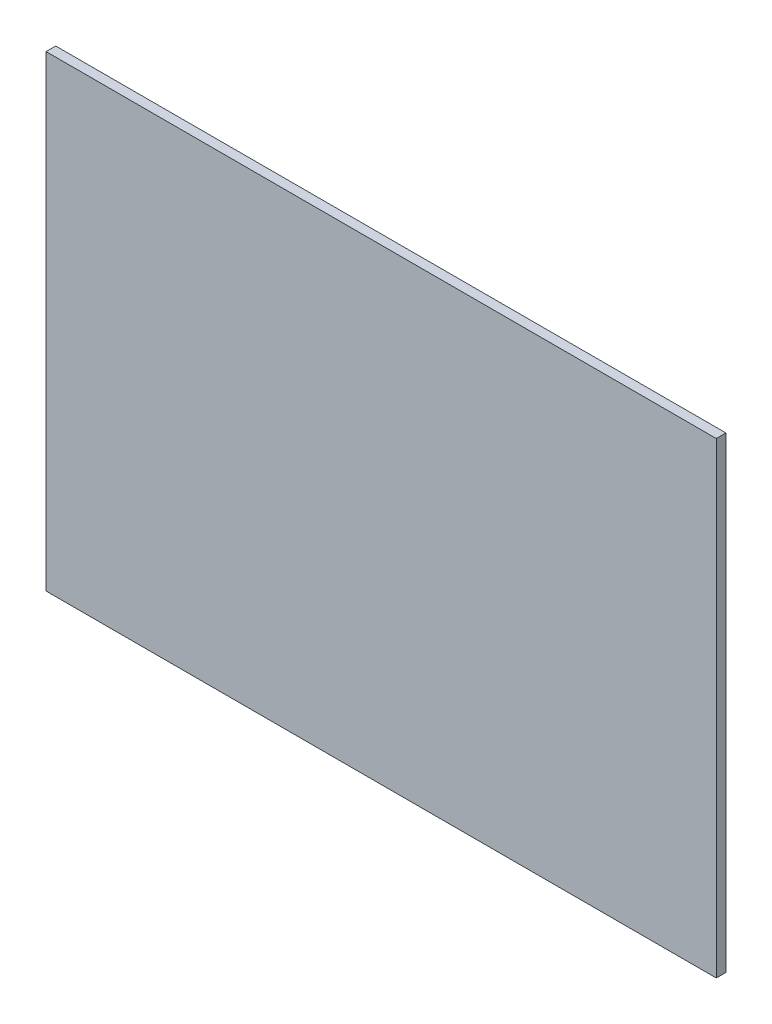
SolidWorks part; units mm, degrees
ref_plane "Alzado" through (0, 0, 0) normal (0, 0, 1) x (1, 0, 0)
ref_plane "Planta" through (0, 0, 0) normal (0, 1, 0) x (1, 0, 0)
ref_plane "Vista lateral" through (0, 0, 0) normal (1, 0, 0) x (0, 0, -1)
sketch "Croquis1" plane through (0, 0, 0) normal (0, 0, 1) x (1, 0, 0)
  line L1 (-95.5677, 99.5185) -> (112.4323, 99.5185)
  line L2 (-95.5677, 99.5185) -> (-95.5677, -45.4815)
  line L3 (-95.5677, -45.4815) -> (112.4323, -45.4815)
  line L4 (112.4323, 99.5185) -> (112.4323, -45.4815)
extrude "Saliente-Extruir1" add sketch "Croquis1" along normal blind 3
